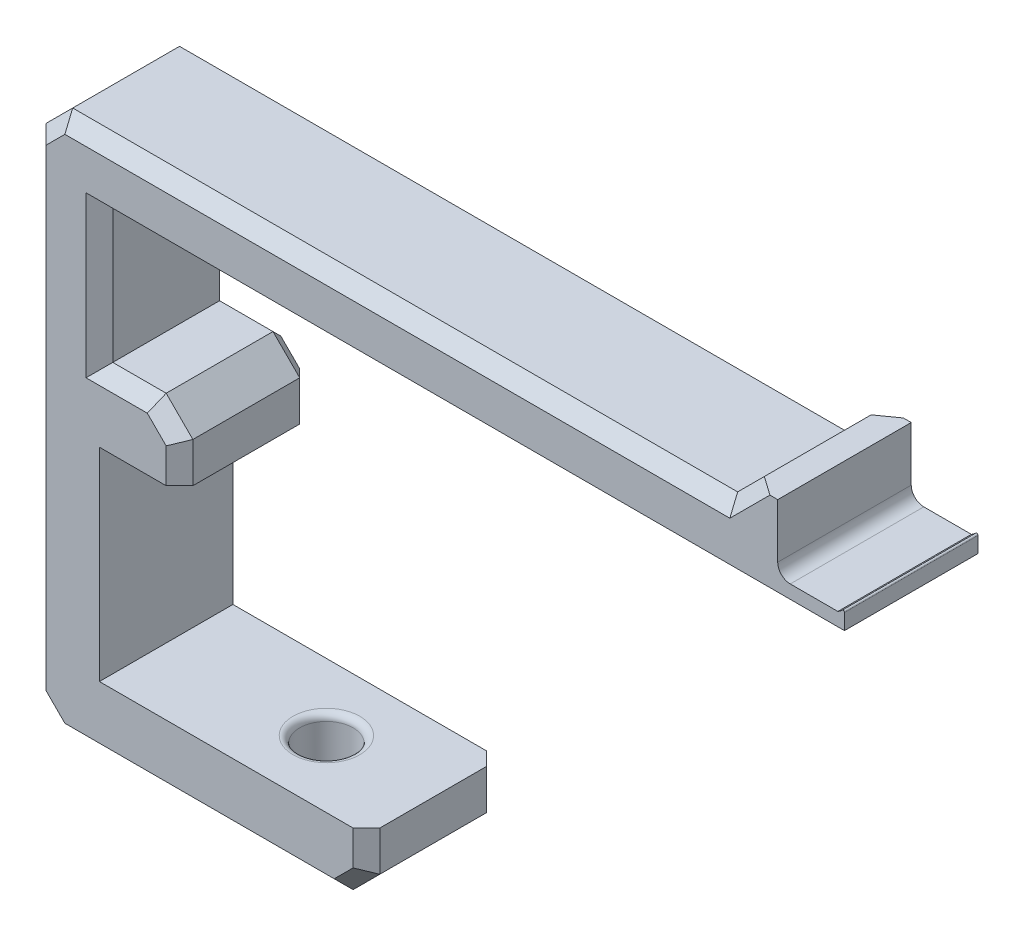
SolidWorks part; units mm, degrees
ref_plane "Plano frontal" through (0, 0, 0) normal (0, 0, 1) x (1, 0, 0)
ref_plane "Plano superior" through (0, 0, 0) normal (0, 1, 0) x (1, 0, 0)
ref_plane "Plano direito" through (0, 0, 0) normal (1, 0, 0) x (0, 0, -1)
sketch "Esboço1" plane through (0, 0, 0) normal (0, 0, 1) x (1, 0, 0)
  line L0 (57, 14.25) -> (1.2, 14.25)
  line L1 (7.2, -0.75) -> (1.2, -0.75)
  line L2 (1.2, 14.25) -> (1.2, 4.25)
  line L3 (1.2, -15.95) -> (21.2, -15.95)
  line L4 (21.2, -15.95) -> (21.2, -20.95)
  line L5 (21.2, -20.95) -> (-3.8, -20.95)
  line L6 (-3.8, -20.95) -> (-3.8, 19.25)
  line L7 (7.2, 4.25) -> (7.2, -0.75)
  line L8 (7.2, 4.25) -> (1.2, 4.25)
  line L9 (1.2, -0.75) -> (1.2, -15.95)
  line L10 (57, 14.25) -> (57, 16.25)
  line L11 (56.5044, 16.25) -> (52, 16.25)
  line L12 (52, 16.25) -> (52, 19.25)
  line L13 (52, 19.25) -> (-3.8, 19.25)
  line L14 (57, 16.25) -> (57, 16.4263)
  arc A0 (57, 16.4263) -> (56.8291, 16.4969) centre (56.9, 16.4263) ccw
  arc A1 (56.5044, 16.25) -> (56.8291, 16.4969) centre (55.7735, 17.5484) ccw
  dimension "D12" = 0.1
  dimension "D1" = 5
  dimension "D2" = 20
  dimension "D3" = 15.2
  dimension "D4" = 6
  dimension "D5" = 5
  dimension "D6" = 5
  dimension "D7" = 2
  dimension "D8" = 5
  dimension "D9" = 10
  dimension "D10" = 55.8
  dimension "D11" = 5
  dimension "D13" = 0.1763
  dimension "D14" = 0.4956
extrude "Ressalto-extrusão1" add sketch "Esboço1" along normal blind 10
sketch "Esboço3" plane through (0, -20.95, 0) normal (0, -1, 0) x (1, 0, 0)
  line L0 (21.2, 5) -> (13.2, 5) construction
  line L1 (21.2, 10) -> (21.2, 0) construction
  circle A0 centre (13.2, 5) radius 2
  dimension "D1" = 4
  dimension "D2" = 8
extrude "Corte-extrusão1" cut sketch "Esboço3" against normal blind 15
chamfer "Chanfro1" distance 1.6 angle 45 1 edges at (13.2, -20.95, 3)
fillet "Filete1" radius 0.5 1 edges at (13.2, -15.95, 3)
fillet "Filete2" radius 0.94 1 edges at (52, 16.25, 5)
sketch "Esboço5" plane through (0, 0, 10) normal (0, 0, 1) x (1, 0, 0)
  line L0 (52, 19.25) -> (52, 21.25)
  line L1 (52, 21.25) -> (50, 21.25)
  line L2 (50, 21.25) -> (48, 19.25)
  line L3 (52, 19.25) -> (-3.8, 19.25) construction
  line L4 (48, 19.25) -> (52, 19.25)
  dimension "D1" = 135
  dimension "D2" = 2
  dimension "D3" = 2
extrude "Ressalto-extrusão3" add sketch "Esboço5" against normal up to surface (10 mm away) up to face at (25.7712, 4.8626, 0)
chamfer "Chanfro5" distance 2 angle 45 4 edges at (21.2, -20.95, 5) (-3.8, -20.95, 5) (-3.8, 19.25, 5) (7.2, 4.25, 5)
chamfer "Chanfro4" distance 1 angle 45 27 edges at (1.2, 9.25, 0) (1.2, 9.25, 10) (29.1, 14.25, 0) (29.1, 14.25, 10) (57, 14.25, 5) (3.2, 4.25, 0) (3.2, 4.25, 10) (49, 20.25, 0) (49, 20.25, 10) (23.1, 19.25, 10) (-2.8, 18.25, 10) (-3.8, -0.85, 10) (-2.8, -19.95, 10) (8.7, -20.95, 10) (20.2, -19.95, 10) (21.2, -17.45, 10) (23.1, 19.25, 0) (-2.8, 18.25, 0) (-3.8, -0.85, 0) (-2.8, -19.95, 0) (8.7, -20.95, 0) (20.2, -19.95, 0) (21.2, -17.45, 0) (6.2, 3.25, 0) (7.2, 0.75, 0) (6.2, 3.25, 10) (7.2, 0.75, 10)
